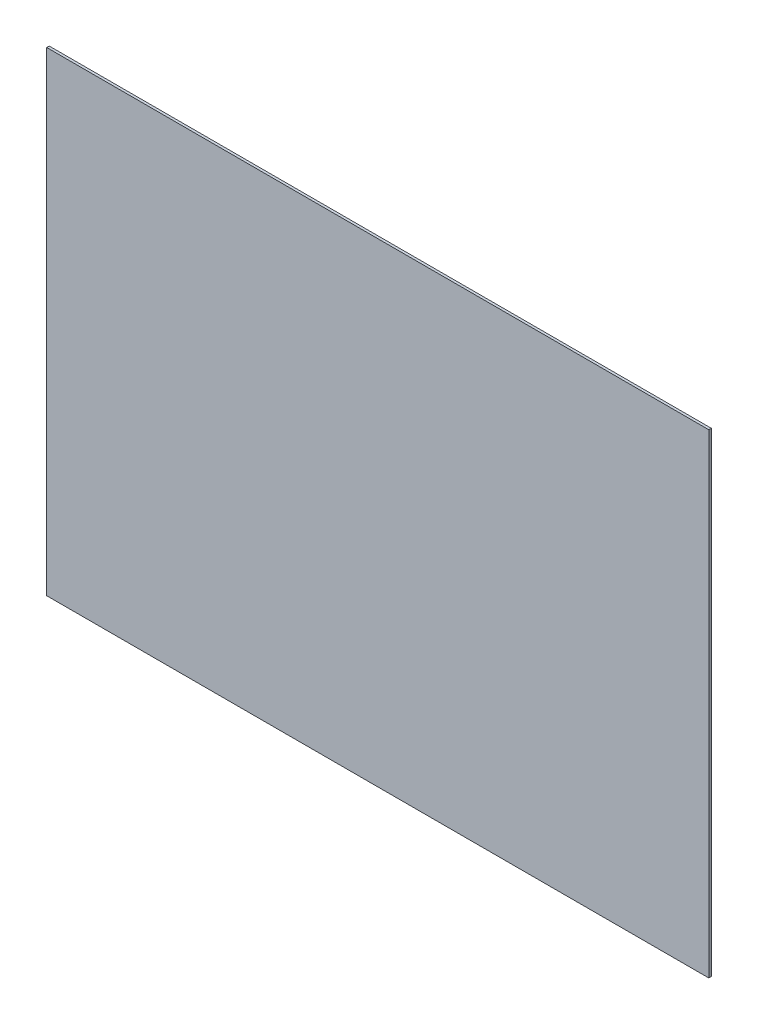
SolidWorks part; units mm, degrees
ref_plane "Alzado" through (0, 0, 0) normal (0, 0, 1) x (1, 0, 0)
ref_plane "Planta" through (0, 0, 0) normal (0, 1, 0) x (1, 0, 0)
ref_plane "Vista lateral" through (0, 0, 0) normal (1, 0, 0) x (0, 0, -1)
sketch "Croquis1" plane through (0, 0, 0) normal (0, 0, 1) x (1, 0, 0)
  line L1 (-625.715, -448.7125) -> (625.715, -448.7125)
  line L2 (-625.715, -448.7125) -> (-625.715, 448.7125)
  line L3 (-625.715, 448.7125) -> (625.715, 448.7125)
  line L4 (625.715, -448.7125) -> (625.715, 448.7125)
  line L5 (-625.715, -448.7125) -> (625.715, 448.7125) construction
  line L6 (-625.715, 448.7125) -> (625.715, -448.7125) construction
  point P0 (0, 0)
  dimension "D1" = 1251.43
  dimension "D2" = 897.425
extrude "Saliente-Extruir1" add sketch "Croquis1" along normal blind 4.7625
